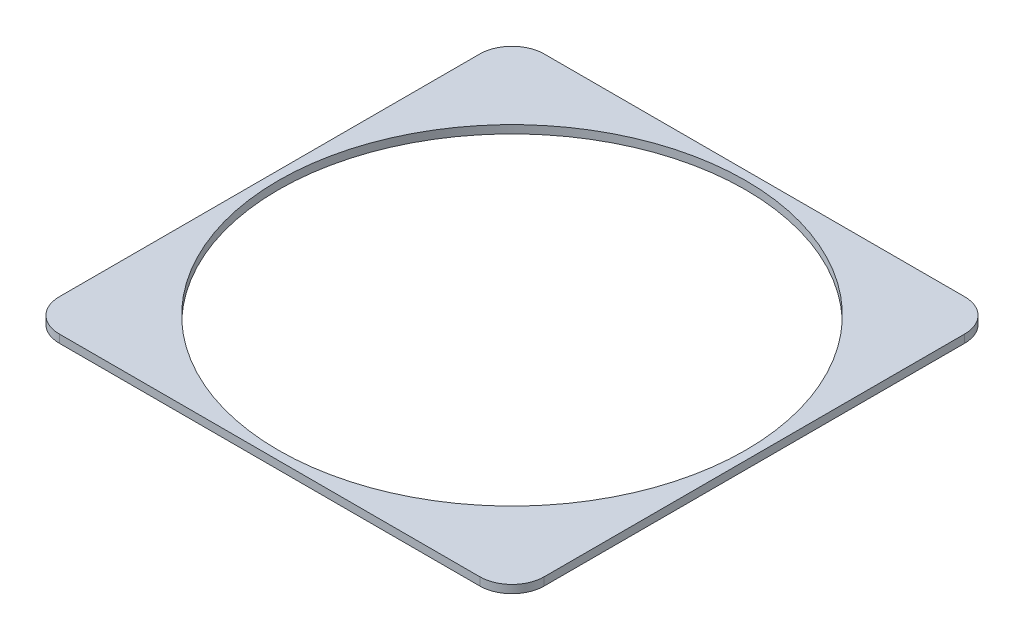
SolidWorks part; units mm, degrees
ref_plane "Front Plane" through (0, 0, 0) normal (0, 0, 1) x (1, 0, 0)
ref_plane "Top Plane" through (0, 0, 0) normal (0, 1, 0) x (1, 0, 0)
ref_plane "Right Plane" through (0, 0, 0) normal (1, 0, 0) x (0, 0, -1)
sketch "Sketch1" plane through (0, 0, 0) normal (0, 1, 0) x (1, 0, 0)
  line L1 (-75.25, -75.25) -> (75.25, -75.25)
  line L2 (-75.25, -75.25) -> (-75.25, 75.25)
  line L3 (-75.25, 75.25) -> (75.25, 75.25)
  line L4 (75.25, -75.25) -> (75.25, 75.25)
  line L5 (-75.25, -75.25) -> (75.25, 75.25) construction
  line L6 (-75.25, 75.25) -> (75.25, -75.25) construction
  circle A0 centre (0, 0) radius 72.5
  dimension "D3" = 145
  dimension "D1" = 150.5
  dimension "D2" = 150.5
extrude "Boss-Extrude1" add sketch "Sketch1" along normal blind 2.5
fillet "Fillet1" radius 10 4 edges at (75.25, 1.25, -75.25) (75.25, 1.25, 75.25) (-75.25, 1.25, 75.25) (-75.25, 1.25, -75.25)
